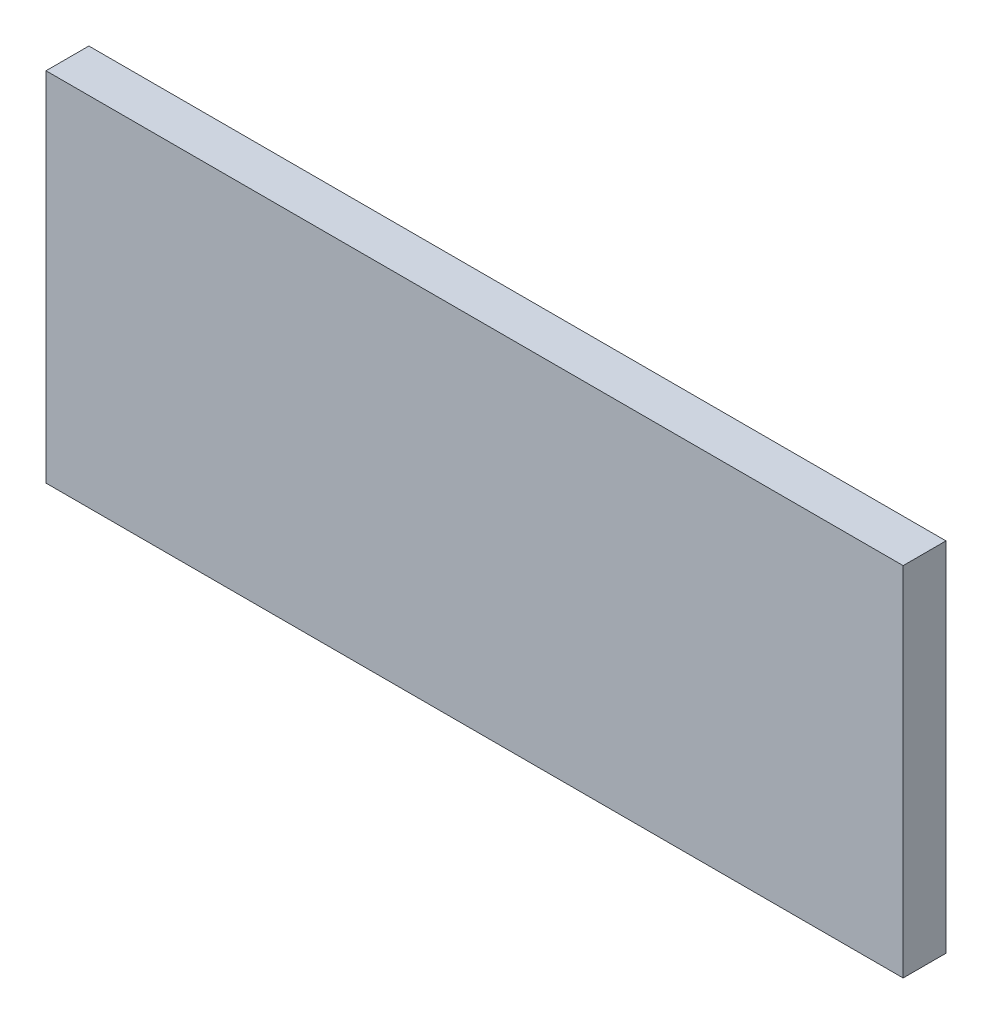
SolidWorks part; units mm, degrees
ref_plane "Front Plane" through (0, 0, 0) normal (0, 0, 1) x (1, 0, 0)
ref_plane "Top Plane" through (0, 0, 0) normal (0, 1, 0) x (1, 0, 0)
ref_plane "Right Plane" through (0, 0, 0) normal (1, 0, 0) x (0, 0, -1)
sketch "Sketch1" plane through (0, 0, 0) normal (0, 0, 1) x (1, 0, 0)
  line L1 (-30, 12.5) -> (30, 12.5)
  line L2 (-30, 12.5) -> (-30, -12.5)
  line L3 (-30, -12.5) -> (30, -12.5)
  line L4 (30, 12.5) -> (30, -12.5)
  line L5 (-30, 12.5) -> (30, -12.5) construction
  line L6 (-30, -12.5) -> (30, 12.5) construction
  point P0 (0, 0)
  dimension "D1" = 25
  dimension "D2" = 60
extrude "Boss-Extrude1" add sketch "Sketch1" along normal blind 3
